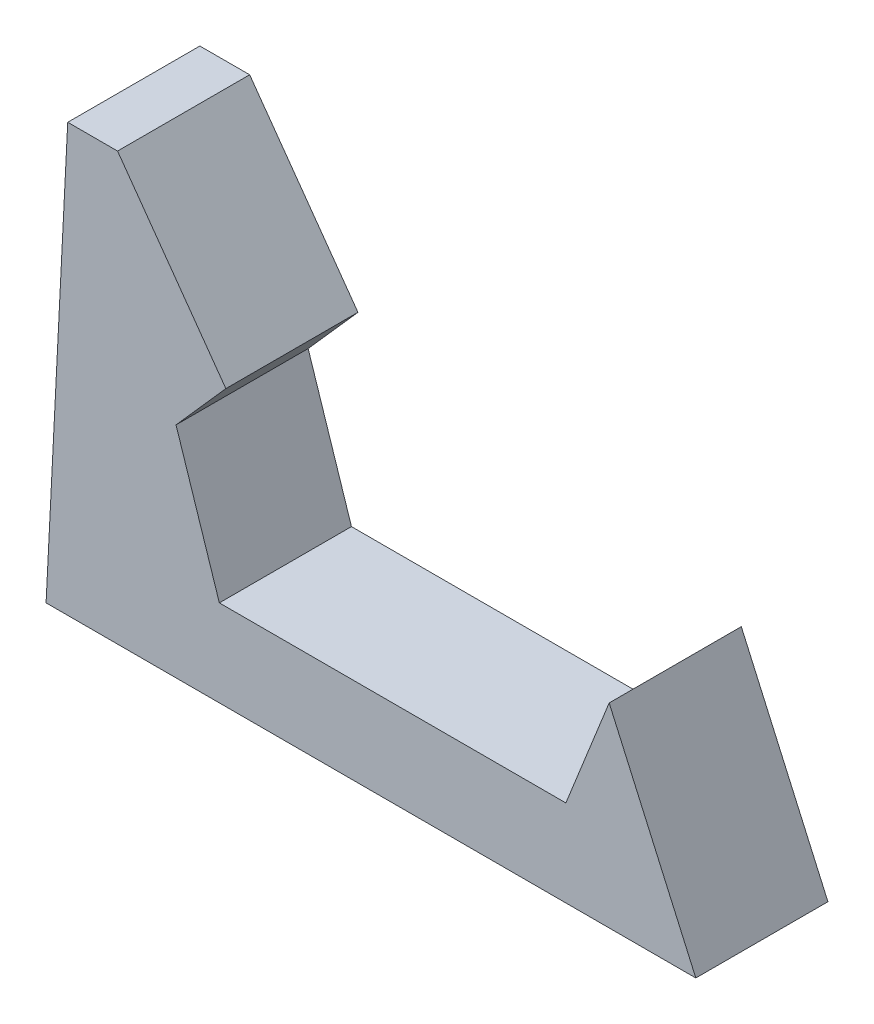
SolidWorks part; units mm, degrees
material "Alloy Steel"
ref_plane "Front Plane" through (0, 0, 0) normal (0, 0, 1) x (1, 0, 0)
ref_plane "Top Plane" through (0, 0, 0) normal (0, 1, 0) x (1, 0, 0)
ref_plane "Right Plane" through (0, 0, 0) normal (1, 0, 0) x (0, 0, -1)
other "Configuration Table"
sketch "Sketch2" plane through (0, 0, 0) normal (0, 0, 1) x (1, 0, 0)
  line L0 (-61.4021, 240.9398) -> (-66.4021, 142.349)
  line L1 (-66.4021, 142.349) -> (83.5979, 142.349)
  line L2 (83.5979, 142.349) -> (63.5979, 187.349)
  line L3 (63.5979, 187.349) -> (53.5979, 162.349)
  line L4 (53.5979, 162.349) -> (-26.4021, 162.349)
  line L5 (-26.4021, 162.349) -> (-36.4021, 192.9398)
  line L6 (-36.4021, 192.9398) -> (-24.9021, 205.9398)
  line L7 (-24.9021, 205.9398) -> (-49.9021, 240.9398)
  line L8 (-49.9021, 240.9398) -> (-61.4021, 240.9398)
  dimension "D1" = 150
  dimension "D2" = 45
  dimension "D3" = 20
  dimension "D4" = 25
  dimension "D5" = 10
  dimension "D6" = 80
  dimension "D7" = 10
  dimension "D8" = 13
  dimension "D10" = 35
  dimension "D11" = 25
  dimension "D12" = 11.5
  dimension "D13" = 5
extrude "Extrude1" add sketch "Sketch2" along normal blind 30.5
